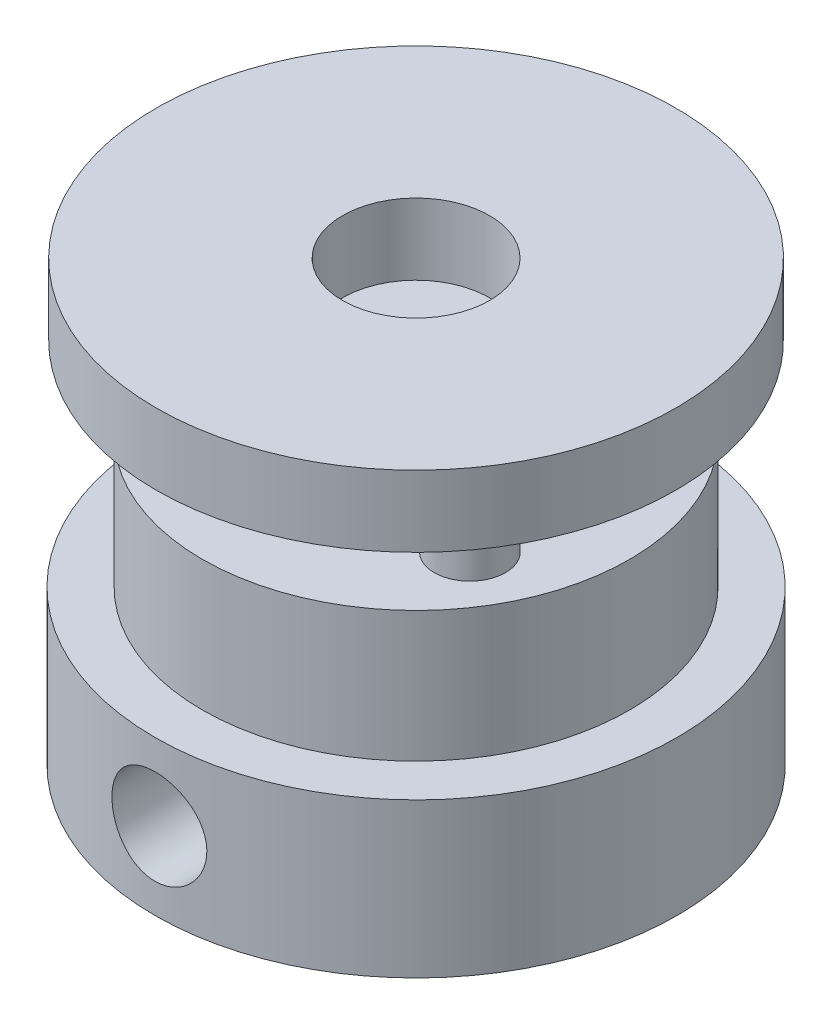
SolidWorks part; units mm, degrees
ref_plane "Front Plane" through (0, 0, 0) normal (0, 0, 1) x (1, 0, 0)
ref_plane "Top Plane" through (0, 0, 0) normal (0, 1, 0) x (1, 0, 0)
ref_plane "Right Plane" through (0, 0, 0) normal (1, 0, 0) x (0, 0, -1)
sketch "Sketch1" plane through (0, 0, 0) normal (0, 1, 0) x (1, 0, 0)
  circle A0 centre (0, 0) radius 11
  dimension "D1" = 22
extrude "Boss-Extrude1" add sketch "Sketch1" along normal blind 6.5
sketch "Sketch2" plane through (0, 6.5, 0) normal (0, 1, 0) x (1, 0, 0)
  circle A0 centre (0, 0) radius 9
  dimension "D1" = 18
extrude "Boss-Extrude2" add sketch "Sketch2" along normal blind 5.5
sketch "Sketch3" plane through (0, 12, 0) normal (0, 1, 0) x (1, 0, 0)
  circle A0 centre (0, 0) radius 3
  dimension "D1" = 6
extrude "Cut-Extrude1" cut sketch "Sketch3" against normal through all
sketch "Sketch4" plane through (0, 12, 0) normal (0, 1, 0) x (1, 0, 0)
  circle A0 centre (0, 6.2) radius 1.5
  point P2 (0, 0)
  dimension "D1" = 3
  dimension "D2" = 6.2
extrude "Boss-Extrude3" add sketch "Sketch4" along normal blind 3.5
pattern_circular "CirPattern1" count 3 over 360 about axis through (0, 0, 0) along (0, 1, 0) of "Boss-Extrude3"
sketch "Sketch5" plane through (0, 15.5, 0) normal (0, 1, 0) x (1, 0, 0)
  circle A0 centre (0, 0) radius 10.95
  circle A1 centre (0, 0) radius 3.1
  dimension "D1" = 21.9
  dimension "D2" = 6.2
extrude "Boss-Extrude4" add sketch "Sketch5" along normal blind 3
sketch "Sketch7" plane through (0, 0, 0) normal (0, 0, 1) x (1, 0, 0)
  circle A0 centre (0, 3.25) radius 2
  point P2 (0, 0)
  dimension "D2" = 4
  dimension "D1" = 3.25
extrude "Cut-Extrude2" cut sketch "Sketch7" along normal through all
